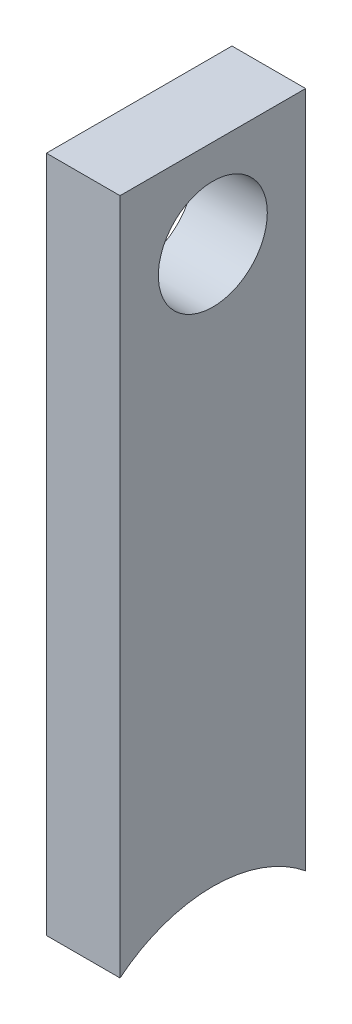
SolidWorks part; units mm, degrees
material "ASTM A36 Steel"
ref_plane "Front Plane" through (0, 0, 0) normal (0, 0, 1) x (1, 0, 0)
ref_plane "Top Plane" through (0, 0, 0) normal (0, 1, 0) x (1, 0, 0)
ref_plane "Right Plane" through (0, 0, 0) normal (1, 0, 0) x (0, 0, -1)
sketch "Sketch1" plane through (0, 0, 0) normal (1, 0, 0) x (0, 0, -1)
  line L2 (-31.5, -115) -> (-31.5, 115)
  line L3 (-31.5, 115) -> (31.5, 115)
  line L4 (31.5, -115) -> (31.5, 115)
  arc A0 (31.5, -115) -> (-31.5, -115) centre (0, -153.8298) ccw
  point P0 (0, 0)
  dimension "D3" = 50
  dimension "D1" = 63
  dimension "D2" = 230
extrude "Boss-Extrude1" add sketch "Sketch1" along normal blind 25
sketch "Sketch2" plane through (25, 0, 0) normal (1, 0, 0) x (0, 0, -1)
  circle A0 centre (0, 85) radius 18.5
  dimension "D1" = 37
  dimension "D2" = 200
extrude "Cut-Extrude1" cut sketch "Sketch2" against normal through all both and the other way through all
